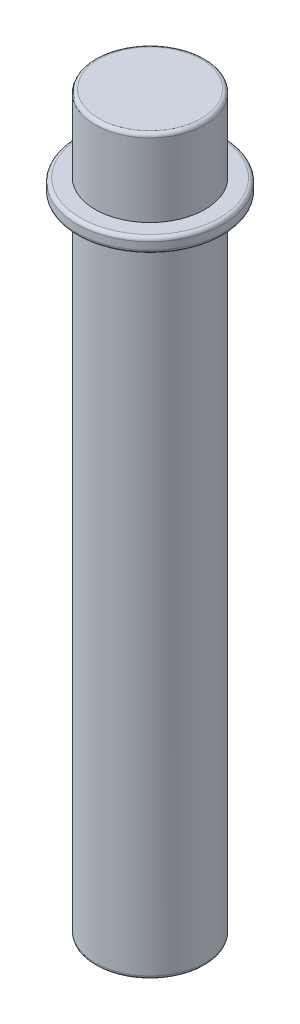
SolidWorks part; units mm, degrees
ref_plane "前视基准面" through (0, 0, 0) normal (0, 0, 1) x (1, 0, 0)
ref_plane "上视基准面" through (0, 0, 0) normal (0, 1, 0) x (1, 0, 0)
ref_plane "右视基准面" through (0, 0, 0) normal (1, 0, 0) x (0, 0, -1)
sketch "草图1" plane through (0, 0, 0) normal (0, 1, 0) x (1, 0, 0)
  circle A0 centre (0, 0) radius 1.5
extrude "凸台-拉伸1" add sketch "草图1" along normal blind 20
sketch "草图2" plane through (0, 20, 0) normal (0, -1, 0) x (1, 0, 0)
  circle A0 centre (0, 0) radius 1.5
  circle A1 centre (0, 0) radius 2
extrude "凸台-拉伸2" add sketch "草图2" along normal blind 0.4 from offset 2.1
fillet "圆角1" radius 0.1 4 edges at (0, 20, 1.5) (0, 0, 1.5) (0, 17.5, -2) (0, 17.9, -2)
